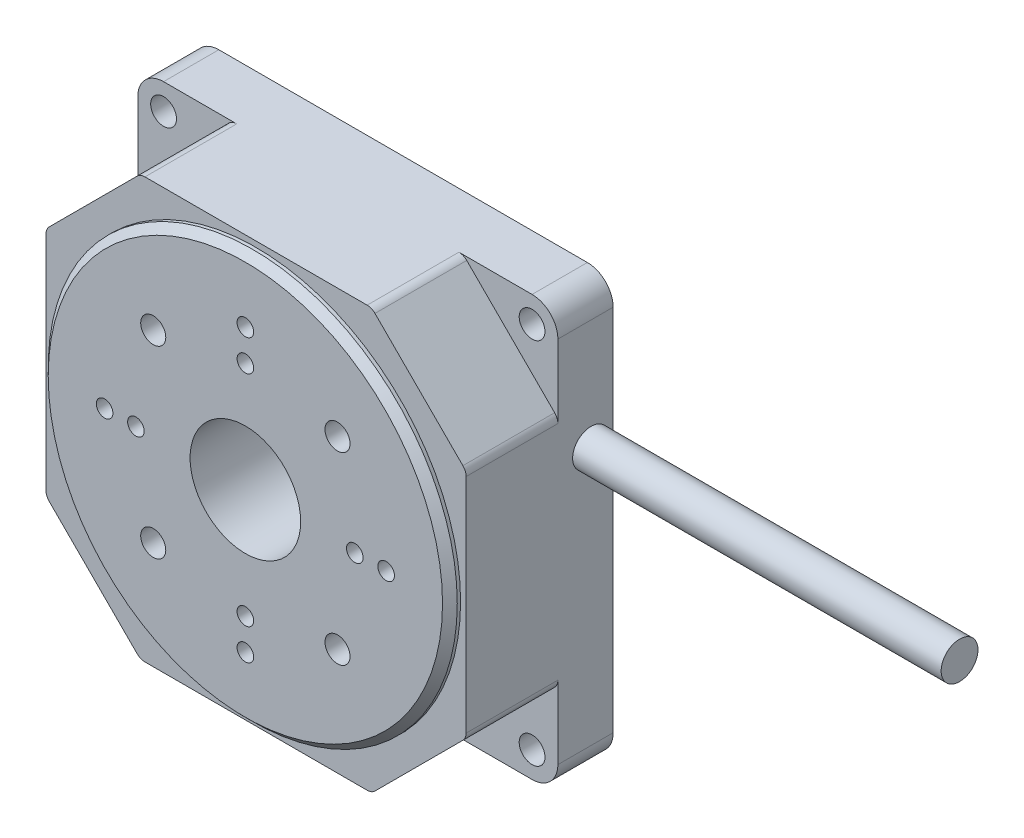
SolidWorks part; units mm, degrees
ref_plane "Front Plane" through (0, 0, 0) normal (0, 0, 1) x (1, 0, 0)
ref_plane "Top Plane" through (0, 0, 0) normal (0, 1, 0) x (1, 0, 0)
ref_plane "Right Plane" through (0, 0, 0) normal (1, 0, 0) x (0, 0, -1)
sketch "Sketch1" plane through (0, 0, 0) normal (0, 0, 1) x (1, 0, 0)
  line L5 (0, 57) -> (0, 0) construction
  line L6 (0, 0) -> (57, 0) construction
  line L7 (-50, 57) -> (50, 57)
  line L8 (57, 50) -> (57, -50)
  line L9 (-57, 50) -> (-57, -50)
  line L10 (-50, -57) -> (50, -57)
  circle A0 centre (50, 50) radius 3.5
  arc A1 (50, 57) -> (57, 50) centre (50, 50) cw
  circle A5 centre (-50, 50) radius 3.5
  arc A6 (-50, 57) -> (-57, 50) centre (-50, 50) ccw
  circle A7 centre (50, -50) radius 3.5
  arc A8 (50, -57) -> (57, -50) centre (50, -50) ccw
  circle A9 centre (-50, -50) radius 3.5
  arc A10 (-50, -57) -> (-57, -50) centre (-50, -50) cw
  point P0 (38.8791, 57)
  point P22 (-57, 0)
  dimension "D1" = 57
  dimension "D3" = 7
  dimension "D2" = 50
extrude "Boss-Extrude1" add sketch "Sketch1" along normal blind 15
sketch "Sketch2" plane through (0, 0, 15) normal (0, 0, 1) x (1, 0, 0)
  line L0 (31.3883, 57) -> (57, 31.3883)
  line L1 (50, 57) -> (-50, 57) construction
  line L2 (57, -50) -> (57, 50) construction
  line L3 (57, 31.3883) -> (57, -31.3883)
  line L4 (57, -31.3883) -> (31.3883, -57)
  line L5 (-50, -57) -> (50, -57) construction
  line L6 (31.3883, -57) -> (-31.3883, -57)
  line L7 (-31.3883, -57) -> (-57, -31.3883)
  line L8 (-57, 50) -> (-57, -50) construction
  line L9 (-57, -31.3883) -> (-57, 31.3883)
  line L10 (-57, 31.3883) -> (-31.3883, 57)
  line L11 (-31.3883, 57) -> (31.3883, 57)
  line L12 (0, 57) -> (0, 0) construction
  point P19 (-20.6582, 57)
  dimension "D1" = 125
extrude "Boss-Extrude2" add sketch "Sketch2" along normal blind 24.9
fillet "Fillet1" radius 3 8 edges at (57, -31.3883, 27.45) (31.3883, -57, 27.45) (-31.3883, -57, 27.45) (-57, -31.3883, 27.45) (57, 31.3883, 27.45) (31.3883, 57, 27.45) (-31.3883, 57, 27.45) (-57, 31.3883, 27.45)
sketch "Sketch3" plane through (57, 0, 0) normal (1, 0, 0) x (0, 0, -1)
  line L0 (0, -50) -> (0, 50) construction
  line L1 (-15, 50) -> (0, 50) construction
  circle A0 centre (-6, 20) radius 5
  point P2 (0, 0)
  point P5 (0, 0)
  dimension "D1" = 6
  dimension "D3" = 10
  dimension "D2" = 30
extrude "Boss-Extrude3" add sketch "Sketch3" along normal blind 100
sketch "Sketch4" plane through (0, 0, 39.9) normal (0, 0, 1) x (1, 0, 0)
  circle A0 centre (0, 0) radius 55.5
  dimension "D1" = 111
extrude "Boss-Extrude4" add sketch "Sketch4" along normal blind 2.9
chamfer "Chamfer1" distance 2 angle 45 1 edges at (55.5, 0, 42.8)
sketch "Sketch5" plane through (0, 0, 42.8) normal (0, 0, 1) x (1, 0, 0)
  line L0 (0, 0) -> (25, 25) construction
  line L1 (-30.1457, -57) -> (30.1457, -57) construction
  line L2 (0, 38.2) -> (0, 0) construction
  circle A0 centre (25, 25) radius 3.4
  circle A1 centre (0, 38.2) radius 2.25
  circle A2 centre (0, 29.7) radius 2.25
  circle A3 centre (38.2, 0) radius 2.25
  circle A4 centre (29.7, 0) radius 2.25
  circle A5 centre (25, -25) radius 3.4
  circle A6 centre (0, -38.2) radius 2.25
  circle A7 centre (0, -29.7) radius 2.25
  circle A8 centre (-25, -25) radius 3.4
  circle A9 centre (-38.2, 0) radius 2.25
  circle A10 centre (-29.7, 0) radius 2.25
  circle A11 centre (-25, 25) radius 3.4
  point P11 (-22.5091, 11.1784)
  point P12 (0, 0)
  point P30 (0, 0)
  dimension "D2" = 6.8
  dimension "D4" = 4.5
  dimension "D1" = 45
  dimension "D3" = 25
  dimension "D5" = 29.7
  dimension "D6" = 38.2
  dimension "D7" = 4
extrude "Cut-Extrude1" cut sketch "Sketch5" against normal blind 5
sketch "Sketch6" plane through (0, 0, 42.8) normal (0, 0, 1) x (1, 0, 0)
  circle A0 centre (0, 0) radius 15
  dimension "D1" = 30
extrude "Cut-Extrude2" cut sketch "Sketch6" against normal up to next
sketch "Sketch7" plane through (0, -57, 0) normal (0, -1, 0) x (1, 0, 0)
  line L0 (0, 39.9) -> (0, 0) construction
  line L1 (-30.1457, 39.9) -> (30.1457, 39.9) construction
  line L2 (-50, 0) -> (50, 0) construction
  line L3 (-25.4, 31.3) -> (-25.4, 5.9) construction
  circle A0 centre (-25.4, 31.3) radius 3.4
  circle A1 centre (-25.4, 5.9) radius 3.4
  circle A2 centre (25.4, 5.9) radius 3.4
  circle A3 centre (25.4, 31.3) radius 3.4
  dimension "D1" = 6.8
  dimension "D2" = 25.4
  dimension "D3" = 5.9
  dimension "D4" = 25.4
extrude "Cut-Extrude3" cut sketch "Sketch7" against normal blind 6
